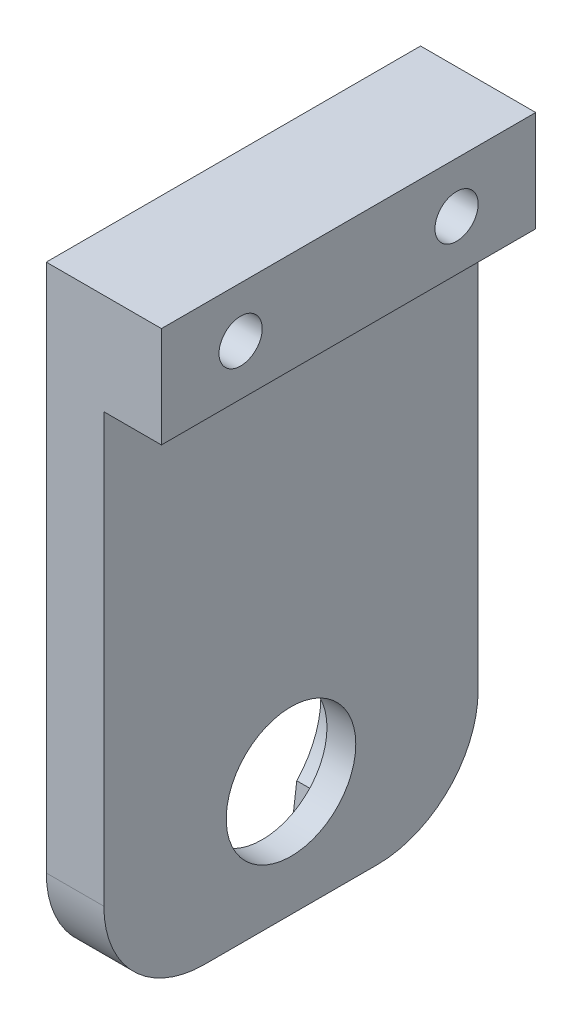
SolidWorks part; units mm, degrees
ref_plane "Спереди" through (0, 0, 0) normal (0, 0, 1) x (1, 0, 0)
ref_plane "Сверху" through (0, 0, 0) normal (0, 1, 0) x (1, 0, 0)
ref_plane "Справа" through (0, 0, 0) normal (1, 0, 0) x (0, 0, -1)
ref_plane "Плоскость4" through (8, 0, 0) normal (1, 0, 0) x (0, 0, -1)
sketch "Эскиз1" plane through (8, 0, 0) normal (1, 0, 0) x (0, 0, -1)
  line L0 (-13, 26.25) -> (-13, -17.5)
  line L1 (-13, -17.5) -> (13, -17.5)
  line L2 (13, -17.5) -> (13, 26.25)
  line L3 (13, 26.25) -> (-13, 26.25)
extrude "Бобышка-Вытянуть1" add sketch "Эскиз1" against normal blind 8
sketch "Эскиз2" plane through (0, 0, 0) normal (-1, 0, 0) x (0, 0, 1)
  line L0 (3.9012, -17.5) -> (4.5455, -13.6524)
  line L1 (4.5455, -5.2103) -> (2.7955, 8.2897)
  line L2 (-2.65, 8.2897) -> (-4.4, -5.2103)
  line L3 (-4.4, -13.6524) -> (-3.9012, -17.5)
  line L4 (-3.9012, -17.5) -> (3.9012, -17.5)
  arc A0 (4.5455, -13.6524) -> (4.5455, -5.2103) centre (0.0727, -9.4314) ccw
  arc A1 (2.7955, 8.2897) -> (-2.65, 8.2897) centre (0.0727, 8.2897) ccw
  arc A2 (-4.4, -5.2103) -> (-4.4, -13.6524) centre (0.0727, -9.4314) ccw
  dimension "D1" = 6.15
  dimension "D2" = 8.9455
extrude "Вырез-Вытянуть1" cut sketch "Эскиз2" against normal blind 2
sketch "Эскиз3" plane through (0, 0, 13) normal (0, 0, 1) x (1, 0, 0)
  line L0 (8, 19.25) -> (4, 19.25)
  line L1 (4, 19.25) -> (4, -17.5)
  line L2 (4, -17.5) -> (8, -17.5)
  line L3 (8, -17.5) -> (8, 19.25)
extrude "Вырез-Вытянуть2" cut sketch "Эскиз3" against normal through all
hole_wizard "Цековка для винта с заклепочной головкой M2.51" positions "Эскиз5" profile "Эскиз4" counterbore size "M2.5" standard "Ansi Metric"
sketch "Эскиз5" plane through (0, 0, 0) normal (-1, 0, 0) x (0, 0, 1)
  point P0 (-7.5, 22.75)
  point P1 (7.5, 22.75)
sketch "Эскиз4" plane through (0, 22.75, -7.5) normal (0, 1, 0) x (0, 0, 1)
  line L0 (0, 0) -> (0, 8)
  line L1 (0, 8) -> (1.5, 8)
  line L3 (1.5, 8) -> (1.5, 1)
  line L4 (1.5, 1) -> (2.75, 1)
  line L5 (2.75, 1) -> (2.75, 0)
  line L7 (2.75, 0) -> (0, 0)
  line L11 (0, -6.35) -> (0, 107.95) construction
  dimension "Диаметр сквозного отверстия" = 3
  dimension "Глубина сквозного отверстия" = 8
  dimension "Диаметр цековки" = 5.5
  dimension "Глубина цековки" = 1
hole_wizard "Диаметр отверстия Ø9.0 (9)1" positions "Эскиз7" profile "Эскиз6" hole size "Ø9.0" standard "Ansi Metric"
sketch "Эскиз7" plane through (4, 0, 0) normal (1, 0, 0) x (0, 0, -1)
  point P0 (0, -9.5)
sketch "Эскиз6" plane through (4, -9.5, 0) normal (0, 1, 0) x (0, 0, -1)
  line L0 (0, 0) -> (0, 4)
  line L1 (0, 4) -> (4.5, 4)
  line L2 (4.5, 4) -> (4.5, 0)
  line L5 (4.5, 0) -> (0, 0)
  line L11 (0, -6.35) -> (0, 107.95) construction
  dimension "Диаметр сквозного отверстия" = 9
  dimension "Глубина сквозного отверстия" = 4
fillet "Скругление1" radius 7 2 edges at (2, -17.5, 13) (2, -17.5, -13)
